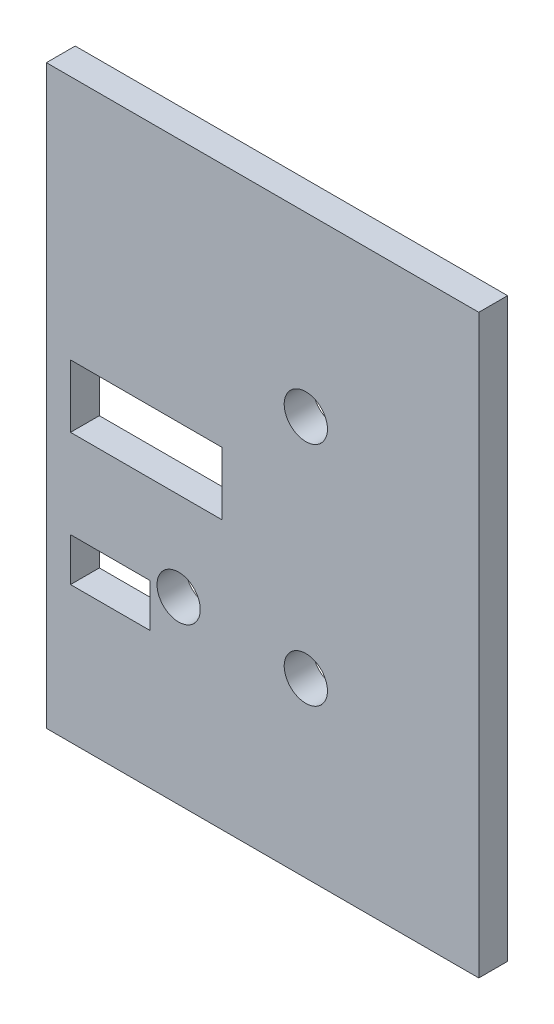
SolidWorks part; units mm, degrees
ref_plane "Front Plane" through (0, 0, 0) normal (0, 0, 1) x (1, 0, 0)
ref_plane "Top Plane" through (0, 0, 0) normal (0, 1, 0) x (1, 0, 0)
ref_plane "Right Plane" through (0, 0, 0) normal (1, 0, 0) x (0, 0, -1)
sketch "Sketch1" plane through (0, 0, 0) normal (0, 0, 1) x (1, 0, 0)
  line L1 (15, -20) -> (-15, -20)
  line L2 (15, -20) -> (15, 20)
  line L3 (15, 20) -> (-15, 20)
  line L4 (-15, -20) -> (-15, 20)
  line L5 (15, -20) -> (-15, 20) construction
  line L6 (15, 20) -> (-15, -20) construction
  point P0 (0, 0)
  dimension "D1" = 40
  dimension "D2" = 30
extrude "Boss-Extrude1" add sketch "Sketch1" along normal blind 2
sketch "Sketch2" plane through (0, 0, 2) normal (0, 0, 1) x (1, 0, 0)
  line L0 (-2.8252, -10.5227) -> (-13.3252, -10.5227)
  line L1 (-2.8252, -10.5227) -> (-2.8252, 2.9773)
  line L2 (-2.8252, 2.9773) -> (-13.3252, 2.9773)
  line L3 (-13.3252, -10.5227) -> (-13.3252, 2.9773)
  line L4 (-2.8252, -10.5227) -> (-13.3252, 2.9773) construction
  line L5 (-2.8252, 2.9773) -> (-13.3252, -10.5227) construction
  line L6 (-2.8252, -1.3763) -> (-13.3252, -1.3763)
  line L7 (-2.8252, -1.3763) -> (-2.8252, 2.9773)
  line L8 (-2.8252, 2.9773) -> (-13.3252, 2.9773)
  line L9 (-13.3252, -1.3763) -> (-13.3252, 2.9773)
  line L10 (-2.8252, -1.3763) -> (-13.3252, 2.9773) construction
  line L11 (-2.8252, 2.9773) -> (-13.3252, -1.3763) construction
  line L12 (-7.8252, -10.5227) -> (-13.3252, -10.5227)
  line L13 (-7.8252, -10.5227) -> (-7.8252, -7.5227)
  line L14 (-7.8252, -7.5227) -> (-13.3252, -7.5227)
  line L15 (-13.3252, -10.5227) -> (-13.3252, -7.5227)
  line L16 (-7.8252, -10.5227) -> (-13.3252, -7.5227) construction
  line L17 (-7.8252, -7.5227) -> (-13.3252, -10.5227) construction
  line L18 (-15, 20) -> (-15, -20) construction
  line L19 (-15, -20) -> (15, -20) construction
  circle A0 centre (-5.8252, -7.5227) radius 1.5
  point P0 (-8.0752, -3.7727)
  point P5 (-8.0752, 0.8005)
  point P6 (-10.5752, -9.0227)
  dimension "D1" = 3
  dimension "D2" = 1.6748
  dimension "D3" = 4.4248
  dimension "D4" = 6.9248
  dimension "D5" = 9.4773
  dimension "D6" = 9.1748
  dimension "D7" = 10.9773
  dimension "D8" = 30
  dimension "D9" = 16.2273
  dimension "D10" = 18.6237
  dimension "D14" = 40
extrude "Cut-Extrude1" cut sketch "Sketch2" against normal blind 2 contours A0 | L13 L14 L3 L0 | L6 L1 L2 L3
sketch "Sketch3" plane through (0, 0, 2) normal (0, 0, 1) x (1, 0, 0)
  line L0 (-15, -20) -> (15, -20) construction
  line L1 (15, -20) -> (15, 20) construction
  circle A0 centre (3, -8) radius 1.5
  circle A1 centre (3, 7.73) radius 1.5
  dimension "D1" = 3
  dimension "D2" = 3
  dimension "D5" = 12
  dimension "D6" = 15.73
  dimension "D3" = 12
  dimension "D4" = 12
extrude "Cut-Extrude2" cut sketch "Sketch3" against normal blind 2
